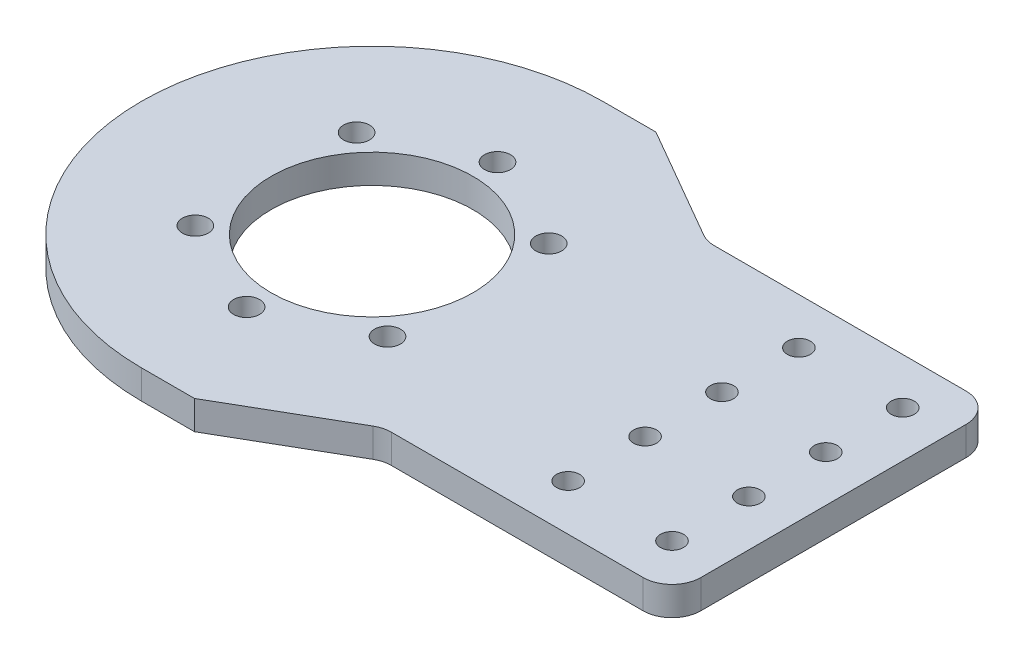
SolidWorks part; units mm, degrees
material "Thornel Mat VMA"
ref_plane "前视基准面" through (0, 0, 0) normal (0, 0, 1) x (1, 0, 0)
ref_plane "上视基准面" through (0, 0, 0) normal (0, 1, 0) x (1, 0, 0)
ref_plane "右视基准面" through (0, 0, 0) normal (1, 0, 0) x (0, 0, -1)
other "Configuration Table"
sketch "草图1" plane through (0, 0, 0) normal (0, 0, 1) x (1, 0, 0)
  line L0 (-270, 0) -> (0, 0)
  dimension "D1" = 270
extrude "拉伸-薄壁1" add sketch "草图1" along normal blind 95 thin
sketch "草图2" plane through (0, 0, 0) normal (0, 1, 0) x (1, 0, 0)
  line L0 (-241.9416, -47.5) -> (53.3701, -47.5) construction
  line L1 (-270, 0) -> (0, 0) construction
  line L2 (-270, -95) -> (0, -95) construction
  line L4 (-246, -47.5) -> (-246, 56.1187) construction
  line L5 (-246, -47.5) -> (-229.3385, -33.5194) construction
  line L7 (-270, -95) -> (-270, 0) construction
  circle A0 centre (-246, -47.5) radius 21.75 construction
  circle A2 centre (-246, -25.75) radius 2.25
  circle A3 centre (-229.3385, -33.5194) radius 2.25
  circle A4 centre (-262.6615, -33.5194) radius 2.25
  circle A5 centre (-262.6615, -61.4806) radius 2.25
  circle A6 centre (-246, -69.25) radius 2.25
  circle A7 centre (-229.3385, -61.4806) radius 2.25
  circle A17 centre (-246, -47.5) radius 17.5
  dimension "D1" = 24
  dimension "D2" = 43.5
  dimension "D4" = 4.5
  dimension "D9" = 35
  dimension "D5" = 50
extrude "切除-拉伸1" cut sketch "草图2" against normal blind 10
sketch "草图3" plane through (0, 0, 0) normal (0, 1, 0) x (1, 0, 0)
  line L0 (30.3557, -47.5) -> (-296.2486, -47.5) construction
  line L1 (-270, 0) -> (0, 0) construction
  line L2 (-270, -95) -> (0, -95) construction
  line L3 (-270, -75) -> (-200, -75)
  line L4 (-270, 0) -> (-200, 0)
  line L5 (-270, 0) -> (-270, -20)
  line L6 (-270, -20) -> (-200, -20)
  line L7 (-200, 0) -> (-200, -20)
  line L8 (-200, -95) -> (-200, -75)
  line L9 (-270, -95) -> (-200, -95)
  line L10 (-270, -95) -> (-270, -75)
  line L11 (-190, -10) -> (-190, -34.7574)
  line L12 (-184.8787, -36.8787) -> (-160.1213, -12.1213)
  line L13 (-162.2426, -7) -> (-187, -7)
  line L17 (-154.1213, -12.1213) -> (-178.8787, -36.8787)
  line L18 (-176.7574, -42) -> (-152, -42)
  line L19 (-149, -39) -> (-149, -14.2426)
  line L20 (-112.2426, -7) -> (-137, -7)
  line L21 (-140, -10) -> (-140, -34.7574)
  line L22 (-134.8787, -36.8787) -> (-110.1213, -12.1213)
  line L23 (-99, -39) -> (-99, -14.2426)
  line L24 (-104.1213, -12.1213) -> (-128.8787, -36.8787)
  line L25 (-126.7574, -42) -> (-102, -42)
  line L26 (-112.2426, -52) -> (-137, -52)
  line L27 (-140, -55) -> (-140, -79.7574)
  line L28 (-134.8787, -81.8787) -> (-110.1213, -57.1213)
  line L29 (-99, -84) -> (-99, -59.2426)
  line L30 (-104.1213, -57.1213) -> (-128.8787, -81.8787)
  line L31 (-126.7574, -87) -> (-102, -87)
  line L32 (-162.2426, -52) -> (-187, -52)
  line L33 (-190, -55) -> (-190, -79.7574)
  line L34 (-184.8787, -81.8787) -> (-160.1213, -57.1213)
  line L35 (-149, -84) -> (-149, -59.2426)
  line L36 (-154.1213, -57.1213) -> (-178.8787, -81.8787)
  line L37 (-176.7574, -87) -> (-152, -87)
  line L38 (-62.2426, -7) -> (-87, -7)
  line L39 (-90, -10) -> (-90, -34.7574)
  line L40 (-84.8787, -36.8787) -> (-60.1213, -12.1213)
  line L41 (-49, -39) -> (-49, -14.2426)
  line L42 (-54.1213, -12.1213) -> (-78.8787, -36.8787)
  line L43 (-76.7574, -42) -> (-52, -42)
  line L44 (-62.2426, -52) -> (-87, -52)
  line L45 (-90, -55) -> (-90, -79.7574)
  line L46 (-84.8787, -81.8787) -> (-60.1213, -57.1213)
  line L47 (-49, -84) -> (-49, -59.2426)
  line L48 (-54.1213, -57.1213) -> (-78.8787, -81.8787)
  line L49 (-76.7574, -87) -> (-52, -87)
  arc A0 (-190, -10) -> (-187, -7) centre (-187, -10) cw
  arc A1 (-152, -42) -> (-149, -39) centre (-152, -39) ccw
  arc A2 (-176.7574, -42) -> (-178.8787, -36.8787) centre (-176.7574, -39) cw
  arc A3 (-149, -14.2426) -> (-154.1213, -12.1213) centre (-152, -14.2426) ccw
  arc A4 (-160.1213, -12.1213) -> (-162.2426, -7) centre (-162.2426, -10) ccw
  arc A5 (-184.8787, -36.8787) -> (-190, -34.7574) centre (-187, -34.7574) cw
  arc A6 (-110.1213, -12.1213) -> (-112.2426, -7) centre (-112.2426, -10) ccw
  arc A7 (-140, -10) -> (-137, -7) centre (-137, -10) cw
  arc A8 (-134.8787, -36.8787) -> (-140, -34.7574) centre (-137, -34.7574) cw
  arc A9 (-99, -14.2426) -> (-104.1213, -12.1213) centre (-102, -14.2426) ccw
  arc A10 (-102, -42) -> (-99, -39) centre (-102, -39) ccw
  arc A11 (-126.7574, -42) -> (-128.8787, -36.8787) centre (-126.7574, -39) cw
  arc A12 (-110.1213, -57.1213) -> (-112.2426, -52) centre (-112.2426, -55) ccw
  arc A13 (-140, -55) -> (-137, -52) centre (-137, -55) cw
  arc A14 (-134.8787, -81.8787) -> (-140, -79.7574) centre (-137, -79.7574) cw
  arc A15 (-99, -59.2426) -> (-104.1213, -57.1213) centre (-102, -59.2426) ccw
  arc A16 (-102, -87) -> (-99, -84) centre (-102, -84) ccw
  arc A17 (-126.7574, -87) -> (-128.8787, -81.8787) centre (-126.7574, -84) cw
  arc A18 (-160.1213, -57.1213) -> (-162.2426, -52) centre (-162.2426, -55) ccw
  arc A19 (-190, -55) -> (-187, -52) centre (-187, -55) cw
  arc A20 (-184.8787, -81.8787) -> (-190, -79.7574) centre (-187, -79.7574) cw
  arc A21 (-149, -59.2426) -> (-154.1213, -57.1213) centre (-152, -59.2426) ccw
  arc A22 (-152, -87) -> (-149, -84) centre (-152, -84) ccw
  arc A23 (-176.7574, -87) -> (-178.8787, -81.8787) centre (-176.7574, -84) cw
  arc A24 (-90, -10) -> (-87, -7) centre (-87, -10) cw
  arc A25 (-84.8787, -36.8787) -> (-90, -34.7574) centre (-87, -34.7574) cw
  arc A26 (-60.1213, -12.1213) -> (-62.2426, -7) centre (-62.2426, -10) ccw
  arc A27 (-49, -14.2426) -> (-54.1213, -12.1213) centre (-52, -14.2426) ccw
  arc A28 (-76.7574, -42) -> (-78.8787, -36.8787) centre (-76.7574, -39) cw
  arc A29 (-52, -42) -> (-49, -39) centre (-52, -39) ccw
  arc A30 (-90, -55) -> (-87, -52) centre (-87, -55) cw
  arc A31 (-84.8787, -81.8787) -> (-90, -79.7574) centre (-87, -79.7574) cw
  arc A32 (-60.1213, -57.1213) -> (-62.2426, -52) centre (-62.2426, -55) ccw
  arc A33 (-49, -59.2426) -> (-54.1213, -57.1213) centre (-52, -59.2426) ccw
  arc A34 (-76.7574, -87) -> (-78.8787, -81.8787) centre (-76.7574, -84) cw
  arc A35 (-52, -87) -> (-49, -84) centre (-52, -84) ccw
  point P20 (-190, -7)
  point P29 (-149, -42)
  point P32 (-184, -42)
  point P35 (-149, -7)
  point P38 (-155, -7)
  point P41 (-190, -42)
  dimension "D10" = 3
  dimension "D1" = 20
  dimension "D2" = 70
  dimension "D3" = 35
  dimension "D4" = 35
  dimension "D5" = 7
  dimension "D6" = 10
  dimension "D7" = 35
  dimension "D8" = 35
  dimension "D9" = 6
  dimension "D13" = 9
  dimension "D14" = 10
  dimension "D16" = 9
  dimension "D11" = 2
  dimension "D12" = 2
  dimension "D15" = 2
extrude "切除-拉伸2" cut sketch "草图3" against normal blind 10
sketch "草图6" plane through (0, 0, 0) normal (0, 1, 0) x (1, 0, 0)
  line L1 (-214.0172, 11.6513) -> (5.847, 11.6513)
  line L2 (-214.0172, 11.6513) -> (-214.0172, -118.0351)
  line L3 (-214.0172, -118.0351) -> (5.847, -118.0351)
  line L4 (5.847, 11.6513) -> (5.847, -118.0351)
extrude "切除-拉伸5" cut sketch "草图6" against normal blind 10
sketch "草图7" plane through (0, 0, 0) normal (0, 1, 0) x (1, 0, 0)
  line L0 (-246, -7.5) -> (-166, -7.5)
  line L1 (-246, -87.5) -> (-166, -87.5)
  line L2 (-166, -7.5) -> (-166, -87.5)
  line L6 (-214.0172, -75) -> (-214.0172, -20)
  line L7 (-214.0172, -20) -> (-270, -20)
  line L8 (-270, -20) -> (-270, -75)
  line L9 (-270, -75) -> (-214.0172, -75)
  line L10 (-214.0172, -75) -> (-214.0172, -20)
  line L11 (-214.0172, -20) -> (-270, -20)
  line L12 (-270, -20) -> (-270, -75)
  line L13 (-270, -75) -> (-214.0172, -75)
  arc A0 (-246, -7.5) -> (-246, -87.5) centre (-246, -47.5) ccw
  circle A1 centre (-246, -47.5) radius 17.5 construction
  dimension "D1" = 80
  dimension "D3" = 80
  dimension "D2" = 0
extrude "凸台-拉伸1" add sketch "草图7" against normal blind 5
sketch "草图9" plane through (0, 0, 0) normal (0, 1, 0) x (1, 0, 0)
  line L1 (-166, -87.5) -> (-166, -7.5) construction
  line L2 (-166, -7.5) -> (-246, -7.5) construction
  line L3 (-246, -87.5) -> (-166, -87.5) construction
  circle A0 centre (-192, -27.5) radius 2
  circle A1 centre (-174, -27.5) radius 2
  circle A2 centre (-174, -40.8333) radius 2
  circle A3 centre (-174, -54.1667) radius 2
  circle A4 centre (-174, -67.5) radius 2
  circle A5 centre (-192, -40.8333) radius 2
  circle A6 centre (-192, -54.1667) radius 2
  circle A7 centre (-192, -67.5) radius 2
  dimension "D1" = 4
  dimension "D2" = 26
  dimension "D5" = 20
  dimension "D6" = 20
  dimension "D7" = 18
  dimension "D8" = 18
  dimension "D3" = 2
  dimension "D4" = 4
extrude "切除-拉伸6" cut sketch "草图9" against normal blind 5
fillet "圆角1" radius 5 2 edges at (-166, -2.5, 87.5) (-166, -2.5, 7.5)
sketch "草图10" plane through (0, 0, 0) normal (0, 1, 0) x (1, 0, 0)
  line L0 (-236.7846, -7.5) -> (-216, -19.5)
  line L1 (-171, -7.5) -> (-246, -7.5) construction
  line L2 (-216, -19.5) -> (-166, -19.5)
  line L3 (-166, -82.5) -> (-166, -12.5) construction
  line L4 (-171, -7.5) -> (-236.7846, -7.5)
  line L5 (-166, -19.5) -> (-166, -12.5)
  line L8 (-315.5723, -47.5) -> (-166, -47.5) construction
  line L9 (-166, -75.5) -> (-166, -82.5)
  line L10 (-171, -87.5) -> (-236.7846, -87.5)
  line L11 (-216, -75.5) -> (-166, -75.5)
  line L12 (-236.7846, -87.5) -> (-216, -75.5)
  arc A0 (-166, -12.5) -> (-171, -7.5) centre (-171, -12.5) ccw construction
  arc A1 (-166, -12.5) -> (-171, -7.5) centre (-171, -12.5) ccw
  arc A3 (-166, -82.5) -> (-171, -87.5) centre (-171, -82.5) cw
  line M20 (-246, -87.5) -> (-171, -87.5)
  arc M21 (-171, -87.5) -> (-166, -82.5) centre (-171, -82.5) ccw
  line M22 (-166, -82.5) -> (-166, -12.5)
  arc M23 (-166, -12.5) -> (-171, -7.5) centre (-171, -12.5) ccw
  line M24 (-171, -7.5) -> (-246, -7.5)
  dimension "D1" = 12
  dimension "D2" = 150
  dimension "D3" = 50
extrude "切除-拉伸7" cut sketch "草图10" against normal blind 5 contours L0 L2 M22 M23 M24 | L12 L11 M20 M21 M22
fillet "圆角2" radius 5 4 edges at (-166, -2.5, 75.5) (-216, -2.5, 75.5) (-216, -2.5, 19.5) (-166, -2.5, 19.5)
